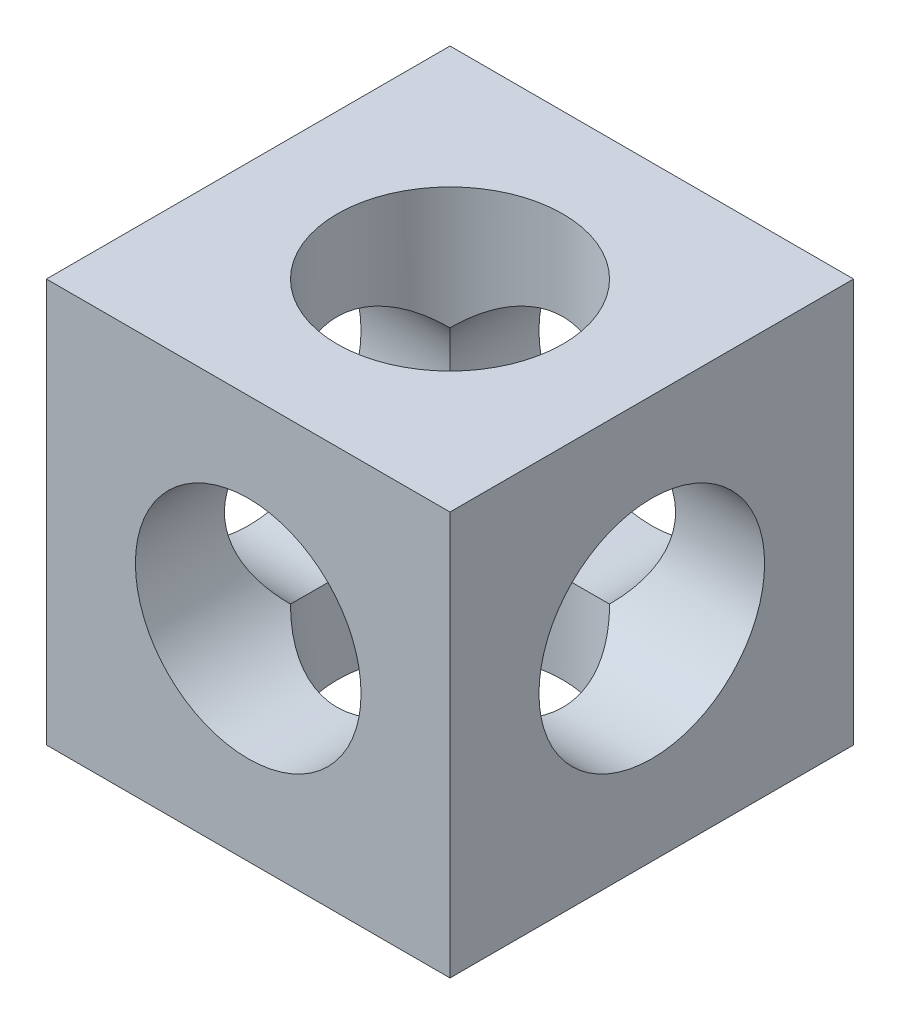
SolidWorks part; units mm, degrees
ref_plane "Front Plane" through (0, 0, 0) normal (0, 0, 1) x (1, 0, 0)
ref_plane "Top Plane" through (0, 0, 0) normal (0, 1, 0) x (1, 0, 0)
ref_plane "Right Plane" through (0, 0, 0) normal (1, 0, 0) x (0, 0, -1)
sketch "Sketch1" plane through (0, 0, 0) normal (0, 1, 0) x (1, 0, 0)
  line L1 (0, 0) -> (12.7, 0)
  line L2 (0, 0) -> (0, 12.7)
  line L3 (0, 12.7) -> (12.7, 12.7)
  line L4 (12.7, 0) -> (12.7, 12.7)
  dimension "D1" = 12.7
  dimension "D2" = 12.7
extrude "Boss-Extrude1" add sketch "Sketch1" along normal blind 12.7
sketch "Sketch2" plane through (0, 12.7, 0) normal (0, 1, 0) x (1, 0, 0)
  line L0 (0, 0) -> (12.7, 12.7) construction
  line L1 (12.7, 12.7) -> (12.7, 0) construction
  line L2 (12.7, 0) -> (0, 12.7) construction
  circle A0 centre (6.35, 6.35) radius 3.55
extrude "Cut-Extrude1" cut sketch "Sketch2" against normal through all
sketch "Sketch3" plane through (12.7, 0, 0) normal (1, 0, 0) x (0, 0, -1)
  line L0 (12.7, 12.7) -> (0, 0) construction
  line L1 (0, 0) -> (12.7, 0) construction
  line L2 (12.7, 0) -> (0, 12.7) construction
  circle A0 centre (6.35, 6.35) radius 3.55
extrude "Cut-Extrude2" cut sketch "Sketch3" against normal through all
sketch "Sketch4" plane through (0, 0, 0) normal (0, 0, 1) x (1, 0, 0)
  line L0 (0, 12.7) -> (12.7, 0) construction
  line L1 (12.7, 0) -> (12.7, 12.7) construction
  line L2 (12.7, 12.7) -> (0, 0) construction
  circle A0 centre (6.35, 6.35) radius 3.55
extrude "Cut-Extrude3" cut sketch "Sketch4" against normal through all
